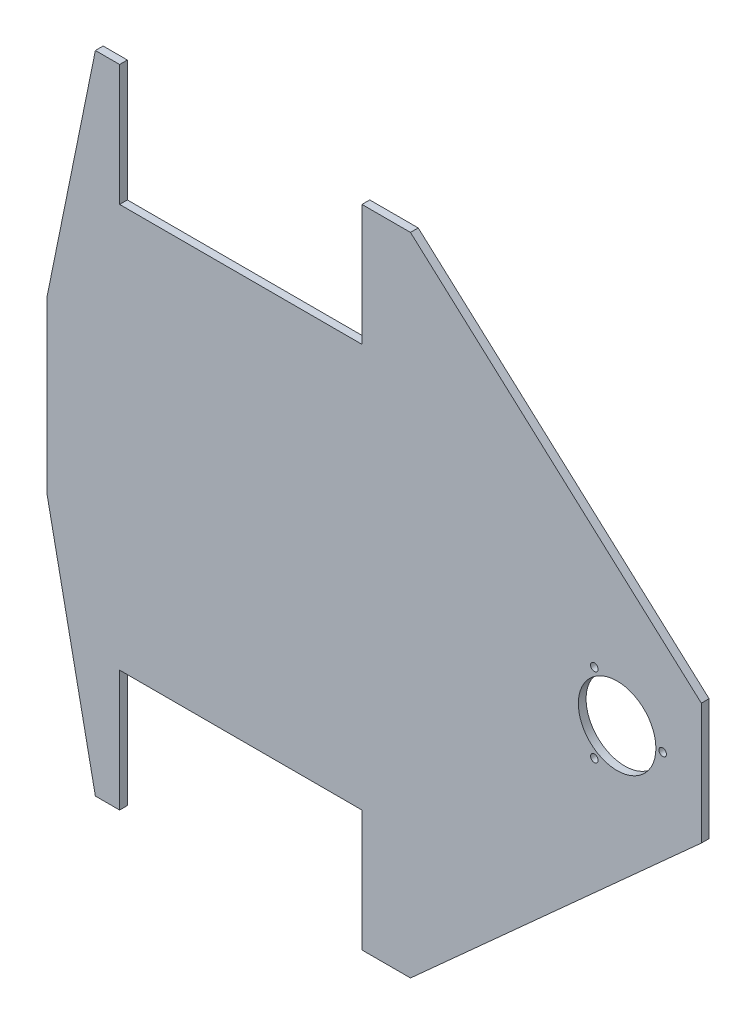
SolidWorks part; units mm, degrees
ref_plane "Спереди" through (0, 0, 0) normal (0, 0, 1) x (1, 0, 0)
ref_plane "Сверху" through (0, 0, 0) normal (0, 1, 0) x (1, 0, 0)
ref_plane "Справа" through (0, 0, 0) normal (1, 0, 0) x (0, 0, -1)
other "Configuration Table"
sketch "Эскиз1" plane through (0, 0, 0) normal (0, 0, 1) x (1, 0, 0)
  line L0 (50, -3.2) -> (-50, -3.2)
  line L1 (-50, -3.2) -> (-50, -53.2)
  line L2 (-50, -53.2) -> (-60, -53.2)
  line L3 (50, -3.2) -> (50, -53.2)
  line L4 (50, -53.2) -> (70, -53.2)
  line L5 (-50, -3.2) -> (-50, 163.2) construction
  line L6 (-53.9564, 80) -> (49946.0436, 80) construction
  line L7 (50, 213.2) -> (70, 213.2)
  line L8 (50, 163.2) -> (50, 213.2)
  line L9 (-50, 213.2) -> (-60, 213.2)
  line L10 (-50, 163.2) -> (-50, 213.2)
  line L11 (50, 163.2) -> (-50, 163.2)
  line L12 (-80, 45) -> (-80, 115)
  line L13 (-60, -53.2) -> (-80, 45)
  line L14 (-80, 115) -> (-60, 213.2)
  line L15 (70, 213.2) -> (190, 105)
  line L16 (190, 105) -> (190, 55)
  line L17 (190, 55) -> (70, -53.2)
  point P22 (-80, 80)
  point P24 (90, 80)
  dimension "D1" = 10
  dimension "D2" = 50
  dimension "D3" = 20
  dimension "D4" = 70
  dimension "D5" = 30
extrude "Бобышка-Вытянуть1" add sketch "Эскиз1" along normal blind 3.2 contours L14 L9 L10 L11 L8 L7 L15 L16 L17 L4 L3 L0 L1 L2 L13 L12
sketch "Эскиз4" plane through (0, 0, 3.2) normal (0, 0, 1) x (1, 0, 0)
  circle A0 centre (155.25, 79.5275) radius 16
  dimension "D1" = 32
extrude "Вырез-Вытянуть1" cut sketch "Эскиз4" against normal blind 6
sketch "Эскиз11" plane through (0, 0, 0) normal (0, 0, -1) x (-1, 0, 0)
  point P0 (-145.85, 63.2463)
  point P1 (-174.05, 79.5275)
  point P3 (-145.85, 95.8088)
  point P5 (0, 0)
  point P7 (0, 0)
hole_wizard "Диаметр отверстия Ø3.1 (3.1)4" positions "Эскиз12" profile "Эскиз13" hole size "Ø3.1" standard "ISO" end condition through all
sketch "Эскиз12" plane through (0, 0, 0) normal (0, 0, -1) x (-1, 0, 0)
  point P0 (-145.85, 95.8088)
  point P3 (-145.85, 63.2463)
  point P6 (-174.05, 79.5275)
sketch "Эскиз13" plane through (145.85, 95.8088, 0) normal (1, 0, 0) x (0, 1, 0)
  line L0 (0, 0) -> (0, 3.2)
  line L1 (0, 3.2) -> (1.55, 3.2)
  line L2 (1.55, 3.2) -> (1.55, 0)
  line L5 (1.55, 0) -> (0, 0)
  line L11 (0, -6.35) -> (0, 107.95) construction
  dimension "Диаметр сквозного отверстия" = 3.1
  dimension "Глубина сквозного отверстия" = 3.2
